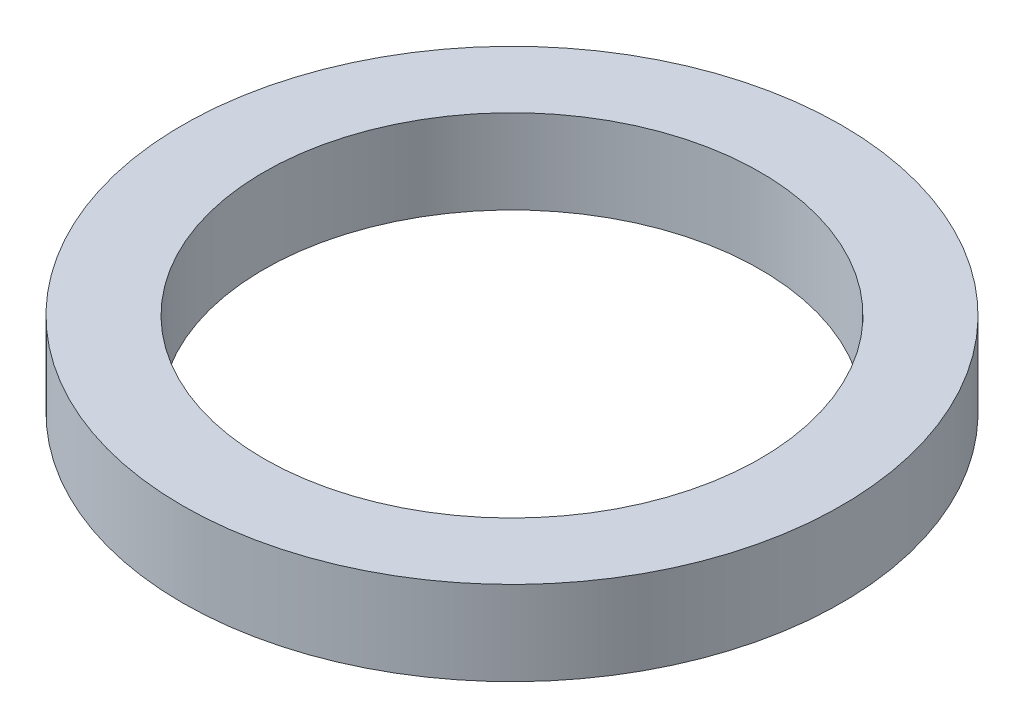
SolidWorks part; units mm, degrees
ref_plane "Front Plane" through (0, 0, 0) normal (0, 0, 1) x (1, 0, 0)
ref_plane "Top Plane" through (0, 0, 0) normal (0, 1, 0) x (1, 0, 0)
ref_plane "Right Plane" through (0, 0, 0) normal (1, 0, 0) x (0, 0, -1)
sketch "Sketch1" plane through (0, 0, 0) normal (0, 1, 0) x (1, 0, 0)
  circle A0 centre (0, 0) radius 29
  circle A1 centre (0, 0) radius 38.505
  dimension "D1" = 58
  dimension "D2" = 77.01
extrude "Boss-Extrude1" add sketch "Sketch1" along normal mid plane 9.84
equation "\"Nr\"= \"Ns\" + 2 * \"Np\"'num teeth"
equation "\"module\"= 0.8"
equation "\"pressure_angle\"= 20deg"
equation "\"h_a\"= 1 * \"module\"'addendum"
equation "\"h_f\"= 1.25 * \"module\"'dedendum"
equation "\"clr_tip_root\"= \"h_f\" - \"h_a\"'clearance of gear tooth tip and root"
equation "\"dp_r\"= \"module\" * \"Nr\"'PCD"
equation "\"db_r\"= \"dp_r\" * cos ( \"pressure_angle\" )'base CD"
equation "\"fw_r\"= 11.5mm'face width"
equation "\"alpha_r\"= sqr ( \"dp_r\" ^ 2 - \"db_r\" ^ 2 ) / \"db_r\" * 180 / pi - \"pressure_angle\""
equation "\"beta_r\"= ( 360 / ( 4 * \"Nr\" ) + \"alpha_r\" ) * 2"
equation "\"bearing_ID\"= \"module\" * ( \"Ns\" + \"Np\" ) + 10"
equation "\"bearing_OD\"= 1.18 * \"bearing_ID\" + 8.57"
equation "\"bearing_height\"= 0.09 * \"bearing_ID\" + 4.62"
equation "\"clearance_planet\"=1.5"
equation "\"case_dist\"= \"sec_carrier_thickness\" + \"clearance_planet\" + \"standard_clearance_1_5mm\""
equation "\"Motor_case_OD_max\"= \"case_mounting_PCD\" + \"case_mounting_hole_allen_socket_dia\" + \"clearance_case_mount_holes_shell_thickness\" * 2"
equation "\"case_mounting_PCD\"= \"motor_case_OD_base\" + \"case_mounting_hole_shift\" * 2"
equation "\"bearing mount thickness\"= IIF((\"bearing_OD\" + \"output_mounting_hole_dia\" * 4) > (\"Nr\" * \"module\" + 2 * \"h_b\"), \"output_mounting_hole_dia\" * 2, ((\"Nr\" * \"module\" + 2 * \"h_b\" - (\"bearing_OD\" + \"output_mounting_hole_dia\" * 4)) / 2) + \"output_mounting_hole_dia\" * 2 + \"standard_clearance_1_5mm\")"
equation "\"case_mounting_hole_dia\"=3"
equation "\"output_mounting_PCD\"= \"bearing_OD\" + \"bearing mount thickness\""
equation "\"output_mounting_hole_dia\"= 4"
equation "\"clearance_case_mount_holes_shell_thickness\"= 1"
equation "\"motor_case_OD_base\"= \"motor_OD\" + \"clearance_motor_and_case\" * 2 + \"Motor_case_thickness\" * 2"
equation "\"sec_carrier_thickness\"= 5"
equation "\"sun_coupler_hub_thickness\"= 4"
equation "\"clearance_sun_coupler_sec_carrier\"= 1.5"
equation "\"clearance_motor_and_case\"= IIF(\"ring_OD\" < \"motor_OD\", 5, (\"ring_OD\" - \"motor_OD\")/2 + 5)"
equation "\"motor_OD\"= 88.6"
equation "\"Motor_case_thickness\"= 2.5"
equation "\"Motor_case_ID\"= \"motor_OD\" + \"clearance_motor_and_case\" * 2"
equation "\"case_mounting_hole_shift\"= \"case_mounting_hole_dia\" / 2 - 0.5"
equation "\"output_mounting_nut_wrench_size\"= 7"
equation "\"output_mounting_nut_thickness\"= 3.2"
equation "\"case_mounting_hole_allen_socket_dia\"= 5.5"
equation "\"output_mounting_nut_depth\"= 3"
equation "\"case_mounting_bolt_depth\"= 4.5"
equation "\"Ns\"= 20"
equation "\"Np\"= 40"
equation "\"ring_radial_thickness\"= 5"
equation "\"ring_OD\"= \"Nr\" * \"module\" + \"ring_radial_thickness\" * 2"
equation "\"ring_to_chamfer_clearance\"= 2"
equation "\"Motor_case_OD_base_to_chamfer\"=5"
equation "\"pattern_offset_from_motor_case_OD_base\"= 3"
equation "\"pattern_bulge_dia\"= 3"
equation "\"pattern_num_bulge\"= 18"
equation "\"pattern_depth\"= 2"
equation "\"motor_height\"= 43"
equation "\"case_mounting_wrench_size\"= 5.5"
equation "\"case_mounting_nut_clearance\"= 2"
equation "\"base_plate_thickness\"= 4"
equation "\"case_mounting_nut_thickness\"= 2.4"
equation "\"case_mounting_surface_height\"= 4"
equation "\"motor_mount_hole_PCD\"= 32"
equation "\"motor_mount_hole_dia\"= 4"
equation "\"motor_mount_hole_num\"= 4"
equation "\"central_hole_offset_from_motor_mount_PCD\"= 5"
equation "\"wire_slot_dist_from_center\"= 30"
equation "\"wire_slot_length\"= 10"
equation "\"wire_slot_radius\"= 4"
equation "\"driver_upper_holes_dist_from_center\"= 23"
equation "\"driver_lower_holes_dist_from_center\"= 15"
equation "\"driver_side_holes_dist_from_center\"= 20"
equation "\"driver_mount_holes_dia\"= 2.5"
equation "\"driver_mount_inserts_OD\"= 3.5"
equation "\"driver_mount_thickness\"= 1.5"
equation "\"driver_mount_height\"= 4"
equation "\"air_flow_hole_offset\"= 3"
equation "\"num_planet\"= 3"
equation "\"planet_pin_bolt_dia\"= 5"
equation "\"planet_pin_socket_head_dia\"= 8.5"
equation "\"carrier_PCD\"= ( \"Np\" + \"Ns\" ) * \"module\""
equation "\"planet_shaft_dia\"= 8"
equation "\"fw_p\"= \"fw_r\""
equation "\"planet_shaft_step_offset\"= 1"
equation "\"carrier_trapezoidal_support_sun_offset\"= 5"
equation "\"carrier_trapezoidal_support_hole_PCD_offset_bearing_ID\"= 4"
equation "\"carrier_trapezoidal_support_hole_dia\"= 3"
equation "\"carrier_trapezoidal_support_hole_socket_head_dia\"= 5.5"
equation "\"carrier_bearing_step_width\"= 1.5"
equation "\"standard_clearance_1_5mm\"=1.5"
equation "\"standard_fillet_1_5mm\"= 1.5"
equation "\"sun_shaft_bearing_OD\"= 16"
equation "\"sun_shaft_bearing_width\"= 4"
equation "\"standard_bearing_insertion_chamfer\"= 0.5"
equation "\"D1@Sketch1\"=\"bearing_ID\""
equation "\"D2@Sketch1\"=\"bearing_OD\""
equation "\"D1@Boss-Extrude1\"=\"bearing_height\""
equation "\"D7@Sketch2\"=\"carrier_trapezoidal_support_hole_dia\""
equation "\"D5@Sketch2\"= 360 / ( 4 * \"Ns\" ) - \"alpha_s\""
equation "\"D3@Sketch2\"=\"dp_s\"- 2*\"h_b\""
equation "\"D9@Sketch2\"=\"carrier_trapezoidal_support_sun_offset\""
equation "\"carrier_trapezoidal_support_hole_wrench_size\"= 5.5"
equation "\"planet_pin_bolt_wrench_size\"= 8"
equation "\"pressure angle\"= 20deg"
equation "\"motor_output_hole_PCD\"= 23"
equation "\"motor_output_hole_dia\"= 4"
equation "\"motor_output_hole_num\"= 4"
equation "\"h_b\"= 1.25 * \"module\"'dedendum"
equation "\"dp_s\"= \"module\" * \"Ns\"'PCD"
equation "\"db_s\"= \"dp_s\" * cos ( \"pressure angle\" )'base CD"
equation "\"fw_s_calc\"= 13mm'face width"
equation "\"alpha_s\"= sqr ( \"dp_s\" ^ 2 - \"db_s\" ^ 2 ) / \"db_s\" * 180 / pi - \"pressure angle\""
equation "\"beta_s\"= ( 360 / ( 4 * \"Ns\" ) - \"alpha_s\" ) * 2"
equation "\"dp_p\"= \"module\" * \"Np\"'PCD"
equation "\"db_p\"= \"dp_p\" * cos ( \"pressure angle\" )'base CD"
equation "\"alpha_p\"= sqr ( \"dp_p\" ^ 2 - \"db_p\" ^ 2 ) / \"db_p\" * 180 / pi - \"pressure angle\""
equation "\"beta_p\"= ( 360 / ( 4 * \"Np\" ) - \"alpha_p\" ) * 2"
equation "\"planet_bearing_OD\"= 12"
equation "\"planet_bearing_width\"= 3"
equation "\"planet_bore\"= 10"
equation "\"sun_shaft_bearing_ID\"= 8"
equation "\"sun_hub_dia\"= \"motor_output_hole_PCD\" + \"motor_output_hole_dia\" + \"standard_clearance_1_5mm\" * 4"
equation "\"sun_central_bolt_dia\"= 5"
equation "\"sun_central_bolt_socket_head_dia\"= 8.5"
equation "\"fw_s_used\"= \"fw_p\" + \"clearance_planet\" + \"sec_carrier_thickness\" + \"standard_clearance_1_5mm\""
equation "\"motor_output_hole_CSK_OD\"= 9'8.96 is exact value"
equation "\"motor_output_hole_CSK_head_height\"= 2.5"
equation "\"bearing_retainer_thickness\"= 2"
equation "\"Ns1\"= 20"
equation "\"Np1\"= 40"
equation "\"Nr1\"= \"Ns1\" + 2 * \"Np1\"'num teeth"
equation "\"module1\"= 0.8"
equation "\"bearing1_ID\"= \"module1\" * ( \"Ns\" + \"Np\" ) + 10"
equation "\"bearing1_OD\"= 1.18 * \"bearing1_ID\" + 8.57"
equation "\"bearing1_height1\"= 0.09 * \"bearing1_ID\" + 4.62"
equation "\"bearing mount thickness1\"= IIF((\"bearing1_OD\" + \"output_mounting_hole_dia\" * 4) > (\"Nr1\" * \"module1\" + 2 * \"module1\"  * 1.25),\"output_mounting_hole_dia\" * 2, ((\"Nr1\" * \"module1\" + 2 * \"module1\"  * 1.25 - (\"bearing1_OD\" + \"output_mounting_hole_dia\" * 4)) / 2) + \"output_mounting_hole_dia\" * 2 + \"standard_clearance_1_5mm\")"
equation "\"output_mounting_PCD1\"= \"bearing1_OD\" + \"bearing mount thickness1\""
